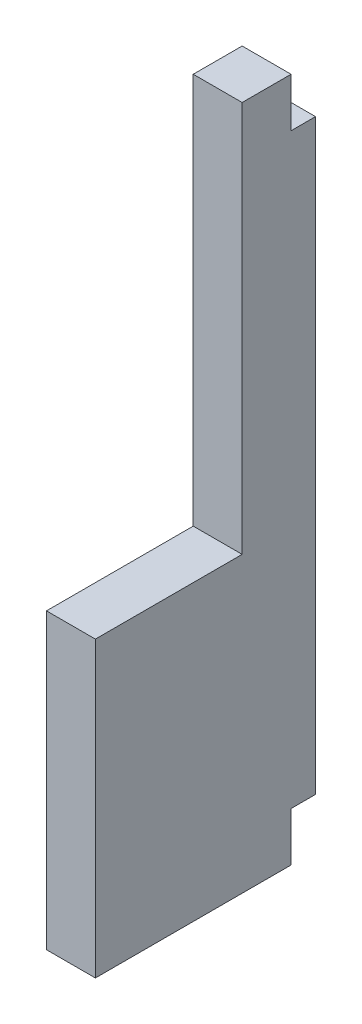
SolidWorks part; units mm, degrees
ref_plane "Front Plane" through (0, 0, 0) normal (0, 0, 1) x (1, 0, 0)
ref_plane "Top Plane" through (0, 0, 0) normal (0, 1, 0) x (1, 0, 0)
ref_plane "Right Plane" through (0, 0, 0) normal (1, 0, 0) x (0, 0, -1)
sketch "Sketch2" plane through (0, 0, 0) normal (1, 0, 0) x (0, 0, -1)
  line L0 (0, 0) -> (0, 80)
  line L1 (0, 80) -> (10, 80)
  line L2 (10, 80) -> (10, 70)
  line L3 (10, 70) -> (15, 70)
  line L4 (15, 70) -> (15, -50)
  line L5 (15, -50) -> (10, -50)
  line L6 (10, -50) -> (10, -60)
  line L7 (10, -60) -> (-30, -60)
  line L8 (-30, -60) -> (-30, 0)
  line L9 (-30, 0) -> (0, 0)
  dimension "D1" = 120
  dimension "D2" = 5
  dimension "D3" = 10
  dimension "D4" = 40
  dimension "D5" = 60
  dimension "D6" = 80
  dimension "D7" = 5
  dimension "D8" = 10
extrude "Boss-Extrude1" add sketch "Sketch2" along normal blind 10
